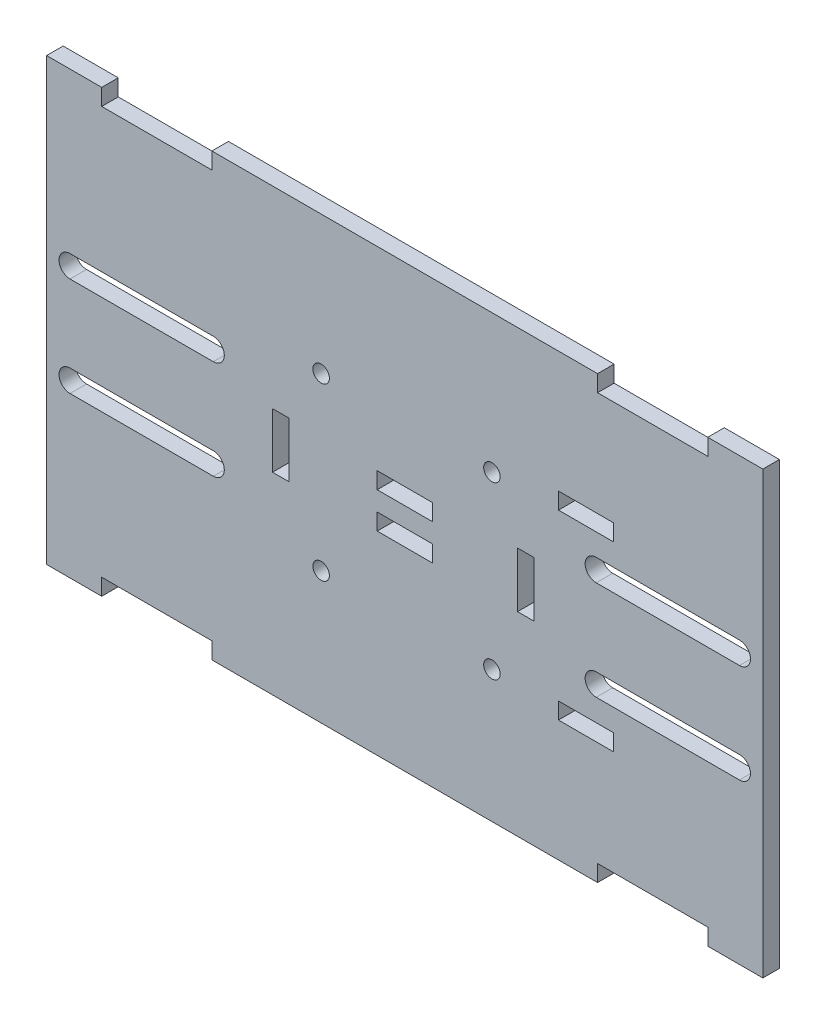
SolidWorks part; units mm, degrees
ref_plane "Front Plane" through (0, 0, 0) normal (0, 0, 1) x (1, 0, 0)
ref_plane "Top Plane" through (0, 0, 0) normal (0, 1, 0) x (1, 0, 0)
ref_plane "Right Plane" through (0, 0, 0) normal (1, 0, 0) x (0, 0, -1)
sketch "Sketch1" plane through (0, 0, 0) normal (0, 0, 1) x (1, 0, 0)
  line L0 (-54.4784, 39.6752) -> (-54.4784, 36.6752)
  line L1 (65.5216, -40.3248) -> (55.5216, -40.3248)
  line L2 (65.5216, -40.3248) -> (65.5216, 39.6752)
  line L3 (65.5216, 39.6752) -> (55.5216, 39.6752)
  line L4 (-64.4784, -40.3248) -> (-64.4784, 39.6752)
  line L5 (65.5216, -40.3248) -> (-64.4784, 39.6752) construction
  line L6 (65.5216, 39.6752) -> (-64.4784, -40.3248) construction
  line L7 (-54.4784, 36.6752) -> (-34.4784, 36.6752)
  line L8 (-34.4784, 36.6752) -> (-34.4784, 39.6752)
  line L9 (35.5216, 39.6752) -> (35.5216, 36.6752)
  line L10 (35.5216, 36.6752) -> (55.5216, 36.6752)
  line L11 (55.5216, 36.6752) -> (55.5216, 39.6752)
  line L12 (-54.4784, -40.3248) -> (-54.4784, -37.3248)
  line L13 (-54.4784, -37.3248) -> (-34.4784, -37.3248)
  line L14 (-34.4784, -37.3248) -> (-34.4784, -40.3248)
  line L15 (35.5216, -40.3248) -> (35.5216, -37.3248)
  line L16 (35.5216, -37.3248) -> (55.5216, -37.3248)
  line L17 (55.5216, -37.3248) -> (55.5216, -40.3248)
  line L18 (-54.4784, 39.6752) -> (-64.4784, 39.6752)
  line L19 (35.5216, 39.6752) -> (-34.4784, 39.6752)
  line L20 (35.5216, -40.3248) -> (-34.4784, -40.3248)
  line L21 (-54.4784, -40.3248) -> (-64.4784, -40.3248)
  line L22 (0.5216, -40.3248) -> (0.5216, 40) construction
  line L23 (-64.4784, -0.3248) -> (65.5216, -0.3248) construction
  line L24 (21, -5) -> (24, -5)
  line L25 (-20.4784, -5.3248) -> (-23.4784, -5.3248)
  line L26 (-20.4784, -5.3248) -> (-20.4784, 4.6752)
  line L27 (-20.4784, 4.6752) -> (-23.4784, 4.6752)
  line L28 (-23.4784, -5.3248) -> (-23.4784, 4.6752)
  line L29 (-20.4784, -5.3248) -> (-23.4784, 4.6752) construction
  line L30 (-20.4784, 4.6752) -> (-23.4784, -5.3248) construction
  line L31 (24, -5) -> (24, 5)
  line L32 (21, 5) -> (24, 5)
  line L33 (21, -5) -> (21, 5)
  line L34 (-60.2284, 10.6752) -> (-34.2284, 10.6752)
  line L35 (16.3477, -16.4008) -> (-14.6523, 14.5992) construction
  line L36 (16.3477, 14.5992) -> (-14.6523, -16.4008) construction
  line L37 (-34.2284, 6.6752) -> (-60.2284, 6.6752)
  line L38 (-34.2284, -7.3248) -> (-60.2284, -7.3248)
  line L39 (-34.2284, -11.3248) -> (-60.2284, -11.3248)
  line L40 (35.2716, 10.6752) -> (61.2716, 10.6752)
  line L41 (61.2716, 6.6752) -> (35.2716, 6.6752)
  line L42 (35.2716, -7.3248) -> (61.2716, -7.3248)
  line L43 (61.2716, -11.3248) -> (35.2716, -11.3248)
  line L44 (28.428, -15.3248) -> (28.428, -18.3248)
  line L45 (38.428, 14.6752) -> (28.428, 14.6752)
  line L46 (38.428, 14.6752) -> (38.428, 17.6752)
  line L47 (38.428, 17.6752) -> (28.428, 17.6752)
  line L48 (28.428, 14.6752) -> (28.428, 17.6752)
  line L49 (38.428, 14.6752) -> (28.428, 17.6752) construction
  line L50 (38.428, 17.6752) -> (28.428, 14.6752) construction
  line L51 (38.428, -15.3248) -> (28.428, -15.3248)
  line L52 (38.428, -15.3248) -> (38.428, -18.3248)
  line L53 (38.428, -18.3248) -> (28.428, -18.3248)
  line L54 (-4.4784, -2.0748) -> (-4.4784, -5.0748)
  line L55 (5.5216, 1.4252) -> (-4.4784, 1.4252)
  line L56 (5.5216, 1.4252) -> (5.5216, 4.4252)
  line L57 (5.5216, 4.4252) -> (-4.4784, 4.4252)
  line L58 (-4.4784, 1.4252) -> (-4.4784, 4.4252)
  line L59 (5.5216, 1.4252) -> (-4.4784, 4.4252) construction
  line L60 (5.5216, 4.4252) -> (-4.4784, 1.4252) construction
  line L61 (5.5216, -2.0748) -> (-4.4784, -2.0748)
  line L62 (5.5216, -2.0748) -> (5.5216, -5.0748)
  line L63 (5.5216, -5.0748) -> (-4.4784, -5.0748)
  arc A0 (-60.2284, 10.6752) -> (-60.2284, 6.6752) centre (-60.2284, 8.6752) ccw
  arc A1 (-60.2284, -11.3248) -> (-60.2284, -7.3248) centre (-60.2284, -9.3248) cw
  arc A2 (-34.2284, 6.6752) -> (-34.2284, 10.6752) centre (-34.2284, 8.6752) ccw
  arc A3 (-34.2284, -7.3248) -> (-34.2284, -11.3248) centre (-34.2284, -9.3248) cw
  arc A4 (35.2716, -7.3248) -> (35.2716, -11.3248) centre (35.2716, -9.3248) ccw
  arc A5 (61.2716, -11.3248) -> (61.2716, -7.3248) centre (61.2716, -9.3248) ccw
  arc A6 (61.2716, 10.6752) -> (61.2716, 6.6752) centre (61.2716, 8.6752) cw
  arc A7 (35.2716, 6.6752) -> (35.2716, 10.6752) centre (35.2716, 8.6752) cw
  circle A8 centre (16.3477, 14.5992) radius 1.5
  circle A9 centre (-14.6523, 14.5992) radius 1.5
  circle A10 centre (16.3477, -16.4008) radius 1.5
  circle A11 centre (-14.6523, -16.4008) radius 1.5
  point P0 (0.5216, -0.3248)
  point P22 (36.5719, 15)
  point P25 (0, 25.5)
  point P26 (-21.9784, -0.3248)
  point P31 (0.8477, -0.9008)
  point P69 (33.428, 16.1752)
  point P80 (33.428, -16.8248)
  point P81 (0.5216, 2.9252)
  dimension "D13" = 4
  dimension "D16" = 4
  dimension "D19" = 3
  dimension "D1" = 130
  dimension "D2" = 10
  dimension "D3" = 3
  dimension "D4" = 20
  dimension "D5" = 10
  dimension "D6" = 80
  dimension "D7" = 10
  dimension "D8" = 10
  dimension "D9" = 20
  dimension "D10" = 3
  dimension "D11" = 10
  dimension "D12" = 18
  dimension "D14" = 60.75
  dimension "D15" = 26
  dimension "D17" = 31
  dimension "D18" = 31
  dimension "D20" = 3
  dimension "D21" = 10
  dimension "D22" = 30
  dimension "D23" = 10
  dimension "D24" = 3
  dimension "D25" = 3.5
extrude "Boss-Extrude1" add sketch "Sketch1" along normal blind 3
